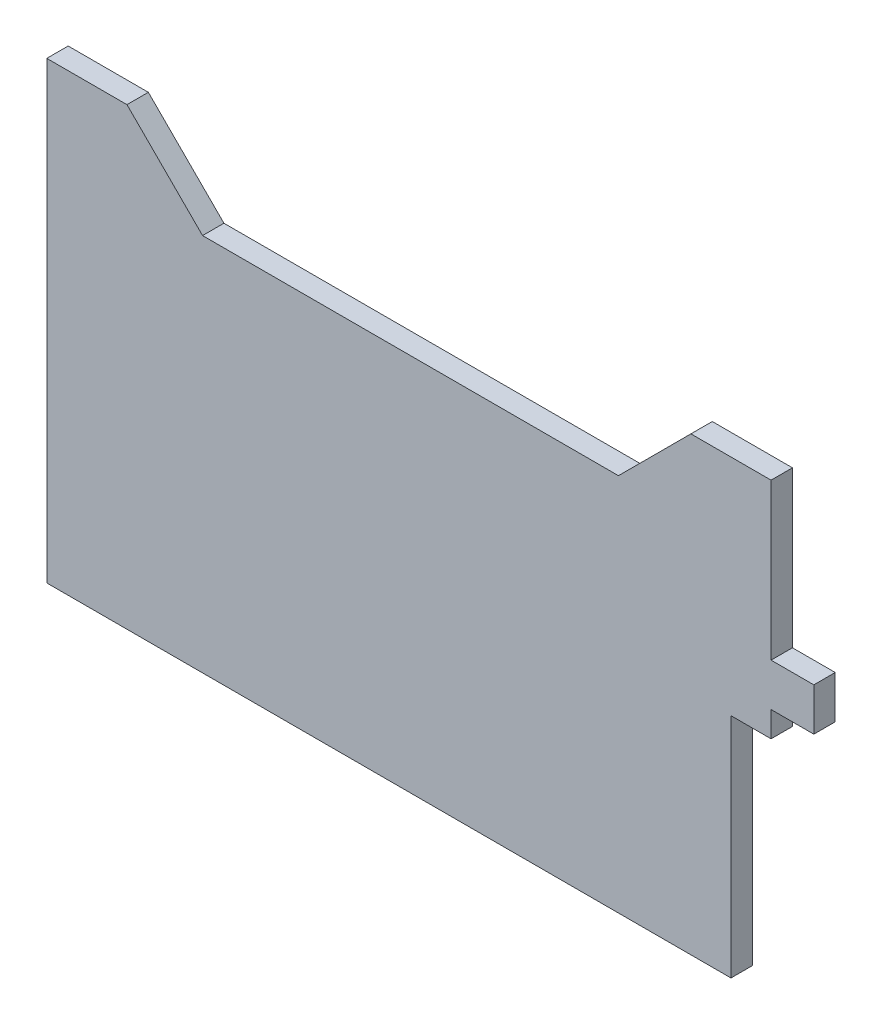
SolidWorks part; units mm, degrees
ref_plane "Front Plane" through (0, 0, 0) normal (0, 0, 1) x (1, 0, 0)
ref_plane "Top Plane" through (0, 0, 0) normal (0, 1, 0) x (1, 0, 0)
ref_plane "Right Plane" through (0, 0, 0) normal (1, 0, 0) x (0, 0, -1)
sketch "Sketch1" plane through (0, 0, 0) normal (0, 0, 1) x (1, 0, 0)
  line L0 (47, 32.2009) -> (54.5, 32.2009)
  line L1 (-81, -27.7991) -> (47, -27.7991)
  line L2 (-81, -27.7991) -> (-81, 32.2009)
  line L3 (-81, 32.2009) -> (47, 32.2009)
  line L4 (47, -27.7991) -> (47, 32.2009) construction
  line L6 (54.5, 14.7009) -> (47, 14.7009)
  line L11 (54.5, 32.2009) -> (54.5, 14.7009) construction
  line L12 (54.5, 32.2009) -> (54.5, 27.4509)
  line L13 (47, 14.7009) -> (47, -27.7991)
  line L14 (54.5, 27.4509) -> (62.5, 27.4509)
  line L15 (62.5, 27.4509) -> (62.5, 19.4509)
  line L16 (62.5, 19.4509) -> (54.5, 19.4509)
  line L17 (54.5, 19.4509) -> (54.5, 14.7009)
  dimension "D3" = 17.5
  dimension "D4" = 7.5
  dimension "D5" = 8
  dimension "D1" = 128
  dimension "D6" = 8
  dimension "D2" = 60
extrude "Boss-Extrude1" add sketch "Sketch1" along normal blind 4
sketch "Sketch2" plane through (0, 0, 0) normal (0, 0, 1) x (1, 0, 0)
  line L0 (-81, 32.2009) -> (54.5, 32.2009)
  line L1 (54.5, 32.2009) -> (54.5, 56.6124)
  line L2 (54.5, 56.6124) -> (39.5, 56.6124)
  line L3 (39.5, 56.6124) -> (25.9463, 43.0588)
  line L4 (25.9463, 43.0588) -> (-51.8579, 43.0588)
  line L5 (-51.8579, 43.0588) -> (-66, 57.2009)
  line L6 (-66, 57.2009) -> (-81, 57.2009)
  line L7 (-81, 57.2009) -> (-81, 32.2009)
  dimension "D1" = 25
  dimension "D2" = 20
  dimension "D3" = 15
  dimension "D4" = 135
extrude "Boss-Extrude2" add sketch "Sketch2" along normal blind 4
